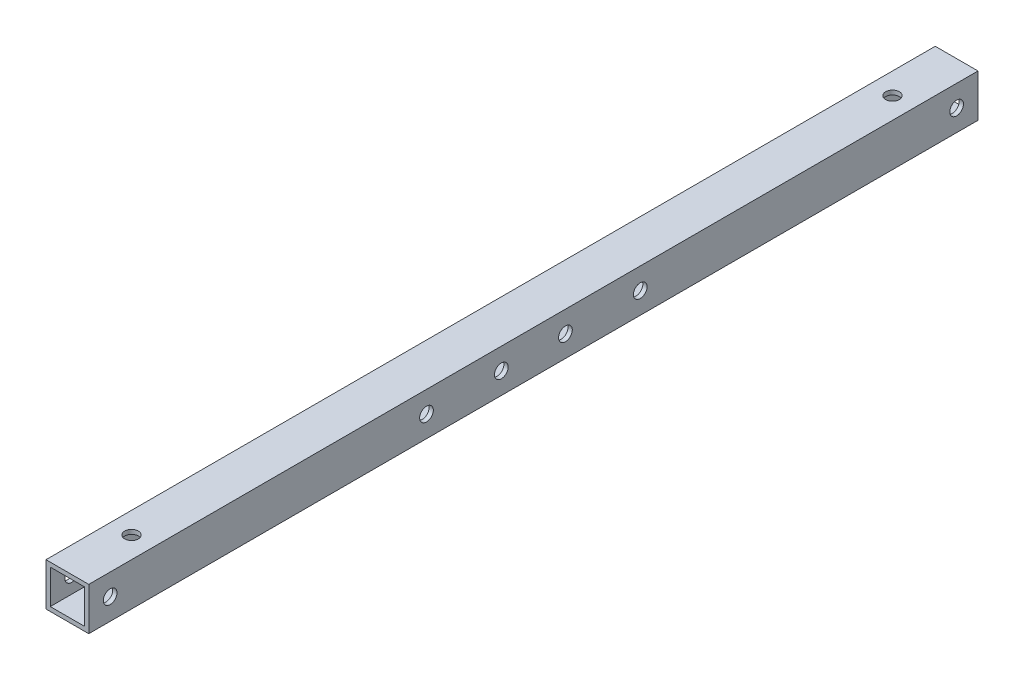
SolidWorks part; units mm, degrees
ref_plane "正面" through (0, 0, 0) normal (0, 0, 1) x (1, 0, 0)
ref_plane "平面" through (0, 0, 0) normal (0, 1, 0) x (1, 0, 0)
ref_plane "右側面" through (0, 0, 0) normal (1, 0, 0) x (0, 0, -1)
sketch "ｽｹｯﾁ1" plane through (0, 0, 0) normal (0, 0, 1) x (1, 0, 0)
  line L0 (-4, 4) -> (-4, -4)
  line L1 (-5, 5) -> (5, 5)
  line L2 (-5, 5) -> (-5, -5)
  line L3 (-5, -5) -> (5, -5)
  line L4 (5, 5) -> (5, -5)
  line L5 (-5, 5) -> (5, -5) construction
  line L6 (-5, -5) -> (5, 5) construction
  line L7 (-4, -4) -> (4, -4)
  line L8 (4, 4) -> (4, -4)
  line L9 (-4, 4) -> (4, 4)
  point P0 (0, 0)
  dimension "D1" = 10
  dimension "D2" = 10
  dimension "D3" = 1
extrude "ﾎﾞｽ - 押し出し1" add sketch "ｽｹｯﾁ1" along normal blind 208
sketch "ｽｹｯﾁ2" plane through (5, 0, 0) normal (1, 0, 0) x (0, 0, -1)
  line L0 (55, 0) -> (-55, 0) construction
  line L1 (-208, -5) -> (-208, 5) construction
  line L2 (0, 55) -> (0, -55) construction
  circle A0 centre (-203, 0) radius 1.6
  circle A1 centre (-111.5, 0) radius 1.6
  circle A2 centre (-96.5, 0) radius 1.6
  circle A3 centre (-5, 0) radius 1.6
  dimension "D1" = 3.2
  dimension "D2" = 3.2
  dimension "D3" = 3.2
  dimension "D4" = 3.2
  dimension "D5" = 5
  dimension "D6" = 5
  dimension "D7" = 15
  dimension "D8" = 96.5
extrude "ｶｯﾄ - 押し出し1" cut sketch "ｽｹｯﾁ2" against normal through all
sketch "ｽｹｯﾁ3" plane through (0, 5, 0) normal (0, 1, 0) x (1, 0, 0)
  line L0 (0, -55) -> (0, 55) construction
  line L1 (5, -208) -> (-5, -208) construction
  line L2 (-55, 0) -> (55, 0) construction
  circle A0 centre (0, -193) radius 1.6
  circle A1 centre (0, -15) radius 1.6
  dimension "D1" = 3.2
  dimension "D2" = 15
  dimension "D3" = 3.2
  dimension "D4" = 15
extrude "ｶｯﾄ - 押し出し2" cut sketch "ｽｹｯﾁ3" against normal through all
sketch "ｽｹｯﾁ4" plane through (5, 0, 0) normal (1, 0, 0) x (0, 0, -1)
  line L0 (5.5, 0) -> (-5.5, 0) construction
  line L1 (-208, -5) -> (-208, 5) construction
  circle A0 centre (-129, 0) radius 1.6
  circle A1 centre (-79, 0) radius 1.6
  dimension "D1" = 3.2
  dimension "D2" = 3.2
  dimension "D3" = 50
  dimension "D4" = 79
extrude "ｶｯﾄ - 押し出し3" cut sketch "ｽｹｯﾁ4" against normal through all
equation "\"D8@ｽｹｯﾁ2\"=104-7.5"
